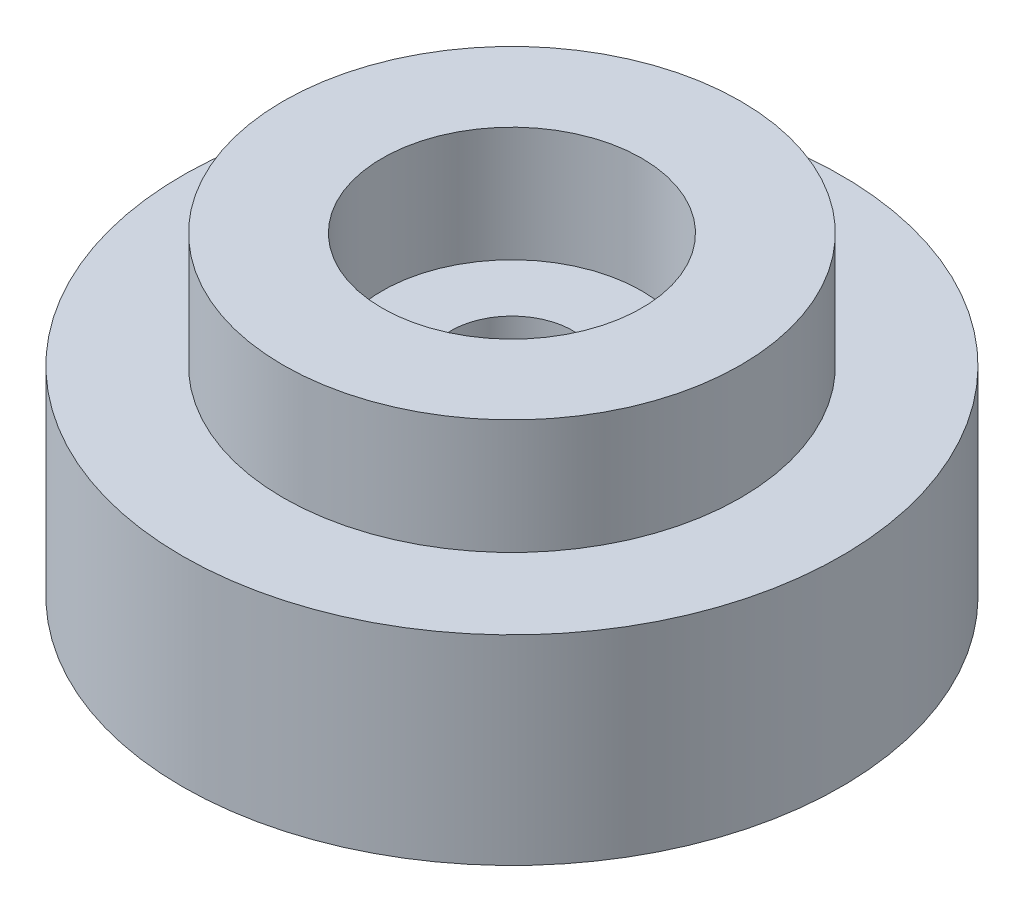
SolidWorks part; units mm, degrees
ref_plane "Front Plane" through (0, 0, 0) normal (0, 0, 1) x (1, 0, 0)
ref_plane "Top Plane" through (0, 0, 0) normal (0, 1, 0) x (1, 0, 0)
ref_plane "Right Plane" through (0, 0, 0) normal (1, 0, 0) x (0, 0, -1)
sketch "Sketch1" plane through (0, 0, 0) normal (0, 1, 0) x (1, 0, 0)
  circle A0 centre (0, 0) radius 16.5
extrude "Boss-Extrude1" add sketch "Sketch1" along normal blind 10
sketch "Sketch2" plane through (0, 10, 0) normal (0, 1, 0) x (1, 0, 0)
  circle A0 centre (0, 0) radius 3.05
extrude "Cut-Extrude1" cut sketch "Sketch2" against normal blind 1.25
sketch "Sketch4" plane through (0, 0, 0) normal (0, 0, 1) x (1, 0, 0)
  line L0 (0, -0.5179) -> (0, 17.9989) construction
  line L1 (16.5, 10) -> (-16.5, 10) construction
  line L2 (6.5, 10) -> (11.45, 10)
  line L3 (6.5, 10) -> (6.5, 15.75)
  line L4 (6.5, 15.75) -> (11.45, 15.75)
  line L5 (11.45, 10) -> (11.45, 15.75)
  dimension "D1" = 6.5
  dimension "D2" = 11.45
  dimension "D3" = 5.75
revolve "Revolve1" add sketch "Sketch4" angle 360 about L0
sketch "Sketch5" plane through (0, 8.75, 0) normal (0, 1, 0) x (1, 0, 0)
  circle A0 centre (0, 0) radius 2
extrude "Cut-Extrude2" cut sketch "Sketch5" against normal through all and the other way through all
